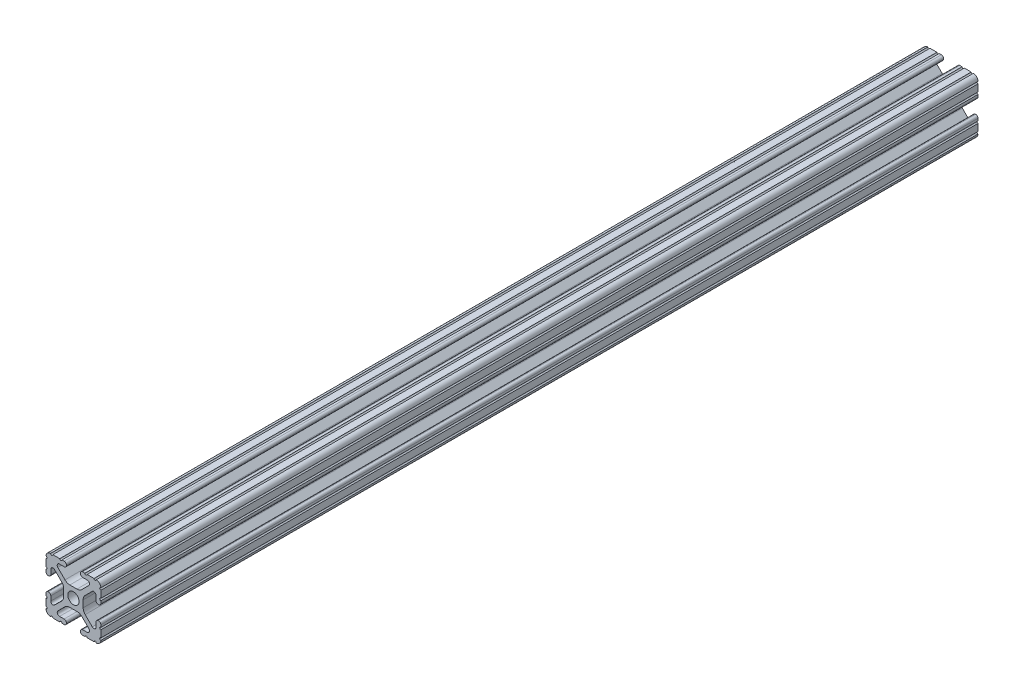
SolidWorks part; units mm, degrees
ref_plane "Front Plane" through (0, 0, 0) normal (0, 0, 1) x (1, 0, 0)
ref_plane "Top Plane" through (0, 0, 0) normal (0, 1, 0) x (1, 0, 0)
ref_plane "Right Plane" through (0, 0, 0) normal (1, 0, 0) x (0, 0, -1)
sketch "Sketch1" plane through (0, 0, 0) normal (0, 0, 1) x (1, 0, 0)
  line L88 (-7.1797, -8.6452) -> (-3.9523, -5.4237)
  line L89 (-1.7093, -4.4958) -> (1.7093, -4.4958)
  line L90 (3.9523, -5.4237) -> (7.1797, -8.6452)
  line L91 (6.4164, -10.4902) -> (4.2875, -10.4902)
  line L92 (3.2385, -11.5392) -> (3.2385, -11.651)
  line L93 (4.2875, -12.7) -> (5.3171, -12.7)
  line L94 (6.3331, -12.7) -> (9.5504, -12.7)
  line L95 (12.7, -9.5504) -> (12.7, -6.3331)
  line L96 (12.7, -5.3171) -> (12.7, -4.2875)
  line L97 (11.651, -3.2385) -> (11.5392, -3.2385)
  line L98 (10.4902, -4.2875) -> (10.4902, -6.4021)
  line L99 (8.7371, -7.1294) -> (5.441, -3.8408)
  line L100 (4.5085, -1.5932) -> (4.5085, 1.5932)
  line L101 (5.441, 3.8408) -> (8.7371, 7.1294)
  line L102 (10.4902, 6.4021) -> (10.4902, 4.2875)
  line L103 (11.5392, 3.2385) -> (11.651, 3.2385)
  line L104 (12.7, 4.2875) -> (12.7, 5.3171)
  line L105 (12.7, 6.3331) -> (12.7, 9.5504)
  line L106 (9.5504, 12.7) -> (6.3331, 12.7)
  line L107 (5.3171, 12.7) -> (4.2875, 12.7)
  line L108 (3.2385, 11.651) -> (3.2385, 11.5392)
  line L109 (4.2875, 10.4902) -> (6.4768, 10.4902)
  line L110 (7.207, 8.7244) -> (3.8983, 5.4232)
  line L111 (1.6558, 4.4958) -> (-1.6558, 4.4958)
  line L112 (-3.8983, 5.4232) -> (-7.207, 8.7244)
  line L113 (-6.4768, 10.4902) -> (-4.2875, 10.4902)
  line L114 (-3.2385, 11.5392) -> (-3.2385, 11.651)
  line L115 (-4.2875, 12.7) -> (-5.3171, 12.7)
  line L116 (-6.3331, 12.7) -> (-9.5504, 12.7)
  line L117 (-12.7, 9.5504) -> (-12.7, 6.3331)
  line L118 (-12.7, 5.3171) -> (-12.7, 4.2875)
  line L119 (-11.651, 3.2385) -> (-11.5392, 3.2385)
  line L120 (-10.4902, 4.2875) -> (-10.4902, 6.4021)
  line L121 (-8.7371, 7.1294) -> (-5.441, 3.8408)
  line L122 (-4.5085, 1.5932) -> (-4.5085, -1.5932)
  line L123 (-5.441, -3.8408) -> (-8.7371, -7.1294)
  line L124 (-10.4902, -6.4021) -> (-10.4902, -4.2875)
  line L125 (-11.5392, -3.2385) -> (-11.651, -3.2385)
  line L126 (-12.7, -4.2875) -> (-12.7, -5.3171)
  line L127 (-12.7, -6.3331) -> (-12.7, -9.5504)
  line L128 (-9.5504, -12.7) -> (-6.3331, -12.7)
  line L129 (-5.3171, -12.7) -> (-4.2875, -12.7)
  line L130 (-3.2385, -11.651) -> (-3.2385, -11.5392)
  line L131 (-4.2875, -10.4902) -> (-6.4164, -10.4902)
  circle A1 centre (0, 0) radius 2.6035
  arc A104 (-7.1797, -8.6452) -> (-6.4164, -10.4902) centre (-6.4164, -9.4098) ccw
  arc A105 (-1.7093, -4.4958) -> (-3.9523, -5.4237) centre (-1.7093, -7.6708) ccw
  arc A106 (3.9523, -5.4237) -> (1.7093, -4.4958) centre (1.7093, -7.6708) ccw
  arc A107 (6.4164, -10.4902) -> (7.1797, -8.6452) centre (6.4164, -9.4098) ccw
  arc A108 (4.2875, -10.4902) -> (3.2385, -11.5392) centre (4.2875, -11.5392) ccw
  arc A109 (3.2385, -11.651) -> (4.2875, -12.7) centre (4.2875, -11.651) ccw
  arc A110 (6.3331, -12.7) -> (5.3171, -12.7) centre (5.8251, -12.7) ccw
  arc A111 (10.5664, -12.6998) -> (9.5504, -12.7) centre (10.0584, -12.7) ccw
  arc A112 (10.5664, -12.6998) -> (12.6998, -10.5664) centre (10.5918, -10.5918) ccw
  arc A113 (12.7, -9.5504) -> (12.6998, -10.5664) centre (12.7, -10.0584) ccw
  arc A114 (12.7, -5.3171) -> (12.7, -6.3331) centre (12.7, -5.8251) ccw
  arc A115 (12.7, -4.2875) -> (11.651, -3.2385) centre (11.651, -4.2875) ccw
  arc A116 (11.5392, -3.2385) -> (10.4902, -4.2875) centre (11.5392, -4.2875) ccw
  arc A117 (8.7371, -7.1294) -> (10.4902, -6.4021) centre (9.4628, -6.4021) ccw
  arc A118 (4.5085, -1.5932) -> (5.441, -3.8408) centre (7.6835, -1.5932) ccw
  arc A119 (5.441, 3.8408) -> (4.5085, 1.5932) centre (7.6835, 1.5932) ccw
  arc A120 (10.4902, 6.4021) -> (8.7371, 7.1294) centre (9.4628, 6.4021) ccw
  arc A121 (10.4902, 4.2875) -> (11.5392, 3.2385) centre (11.5392, 4.2875) ccw
  arc A122 (11.651, 3.2385) -> (12.7, 4.2875) centre (11.651, 4.2875) ccw
  arc A123 (12.7, 6.3331) -> (12.7, 5.3171) centre (12.7, 5.8251) ccw
  arc A124 (12.6998, 10.5664) -> (12.7, 9.5504) centre (12.7, 10.0584) ccw
  arc A125 (12.6998, 10.5664) -> (10.5664, 12.6998) centre (10.5918, 10.5918) ccw
  arc A126 (9.5504, 12.7) -> (10.5664, 12.6998) centre (10.0584, 12.7) ccw
  arc A127 (5.3171, 12.7) -> (6.3331, 12.7) centre (5.8251, 12.7) ccw
  arc A128 (4.2875, 12.7) -> (3.2385, 11.651) centre (4.2875, 11.651) ccw
  arc A129 (3.2385, 11.5392) -> (4.2875, 10.4902) centre (4.2875, 11.5392) ccw
  arc A130 (7.207, 8.7244) -> (6.4768, 10.4902) centre (6.4768, 9.4563) ccw
  arc A131 (1.6558, 4.4958) -> (3.8983, 5.4232) centre (1.6558, 7.6708) ccw
  arc A132 (-3.8983, 5.4232) -> (-1.6558, 4.4958) centre (-1.6558, 7.6708) ccw
  arc A133 (-6.4768, 10.4902) -> (-7.207, 8.7244) centre (-6.4768, 9.4563) ccw
  arc A134 (-4.2875, 10.4902) -> (-3.2385, 11.5392) centre (-4.2875, 11.5392) ccw
  arc A135 (-3.2385, 11.651) -> (-4.2875, 12.7) centre (-4.2875, 11.651) ccw
  arc A136 (-6.3331, 12.7) -> (-5.3171, 12.7) centre (-5.8251, 12.7) ccw
  arc A137 (-10.5664, 12.6998) -> (-9.5504, 12.7) centre (-10.0584, 12.7) ccw
  arc A138 (-10.5664, 12.6998) -> (-12.6998, 10.5664) centre (-10.5918, 10.5918) ccw
  arc A139 (-12.7, 9.5504) -> (-12.6998, 10.5664) centre (-12.7, 10.0584) ccw
  arc A140 (-12.7, 5.3171) -> (-12.7, 6.3331) centre (-12.7, 5.8251) ccw
  arc A141 (-12.7, 4.2875) -> (-11.651, 3.2385) centre (-11.651, 4.2875) ccw
  arc A142 (-11.5392, 3.2385) -> (-10.4902, 4.2875) centre (-11.5392, 4.2875) ccw
  arc A143 (-8.7371, 7.1294) -> (-10.4902, 6.4021) centre (-9.4628, 6.4021) ccw
  arc A144 (-4.5085, 1.5932) -> (-5.441, 3.8408) centre (-7.6835, 1.5932) ccw
  arc A145 (-5.441, -3.8408) -> (-4.5085, -1.5932) centre (-7.6835, -1.5932) ccw
  arc A146 (-10.4902, -6.4021) -> (-8.7371, -7.1294) centre (-9.4628, -6.4021) ccw
  arc A147 (-10.4902, -4.2875) -> (-11.5392, -3.2385) centre (-11.5392, -4.2875) ccw
  arc A148 (-11.651, -3.2385) -> (-12.7, -4.2875) centre (-11.651, -4.2875) ccw
  arc A149 (-12.7, -6.3331) -> (-12.7, -5.3171) centre (-12.7, -5.8251) ccw
  arc A150 (-12.6998, -10.5664) -> (-12.7, -9.5504) centre (-12.7, -10.0584) ccw
  arc A151 (-12.6998, -10.5664) -> (-10.5664, -12.6998) centre (-10.5918, -10.5918) ccw
  arc A152 (-9.5504, -12.7) -> (-10.5664, -12.6998) centre (-10.0584, -12.7) ccw
  arc A153 (-5.3171, -12.7) -> (-6.3331, -12.7) centre (-5.8251, -12.7) ccw
  arc A154 (-4.2875, -12.7) -> (-3.2385, -11.651) centre (-4.2875, -11.651) ccw
  arc A155 (-3.2385, -11.5392) -> (-4.2875, -10.4902) centre (-4.2875, -11.5392) ccw
extrude "Boss-Extrude1" add sketch "Sketch1" along normal mid plane 406.4
equation "\"deep\"= 6in"
equation "\"high\"= 24in"
equation "\"wide\" = 14in"
equation "\"Length@Boss-Extrude1\"  = \"front wide\""
equation "\"front wide\"= 16in"
